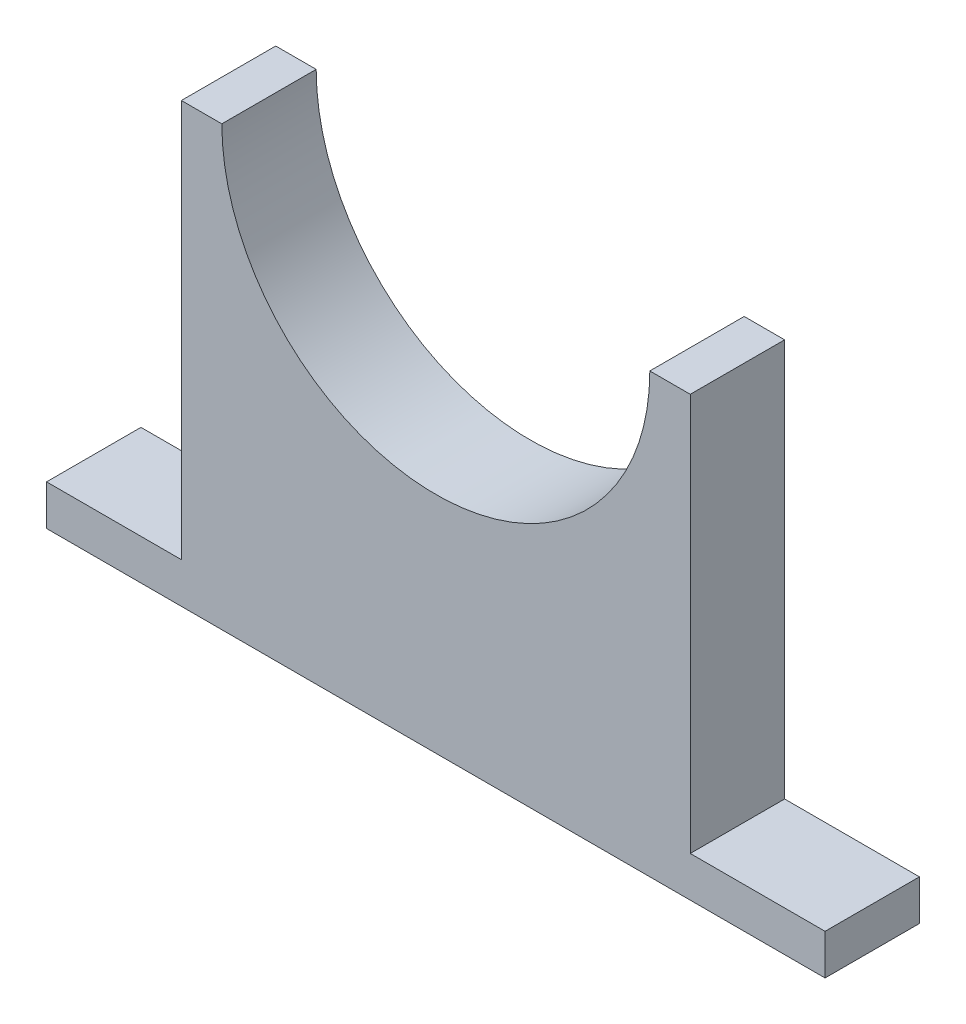
SolidWorks part; units mm, degrees
ref_plane "Front Plane" through (0, 0, 0) normal (0, 0, 1) x (1, 0, 0)
ref_plane "Top Plane" through (0, 0, 0) normal (0, 1, 0) x (1, 0, 0)
ref_plane "Right Plane" through (0, 0, 0) normal (1, 0, 0) x (0, 0, -1)
sketch "Sketch1" plane through (0, 0, 0) normal (0, 0, 1) x (1, 0, 0)
  line L0 (-15.875, 0) -> (-18.875, 0)
  line L1 (-18.875, 0) -> (-18.875, -29.5)
  line L2 (-18.875, -29.5) -> (-28.875, -29.5)
  line L3 (-28.875, -29.5) -> (-28.875, -32.5)
  line L4 (-28.875, -32.5) -> (28.875, -32.5)
  line L5 (28.875, -32.5) -> (28.875, -29.5)
  line L6 (28.875, -29.5) -> (18.875, -29.5)
  line L7 (18.875, -29.5) -> (18.875, 0)
  line L8 (18.875, 0) -> (15.875, 0)
  arc A0 (-15.875, 0) -> (15.875, 0) centre (0, 0) ccw
  dimension "D1" = 31.75
  dimension "D2" = 29.5
  dimension "D3" = 3
  dimension "D4" = 10
  dimension "D5" = 3
extrude "Boss-Extrude1" add sketch "Sketch1" along normal blind 7
equation "\"D2@Sketch1\"=15.82+13.68"
